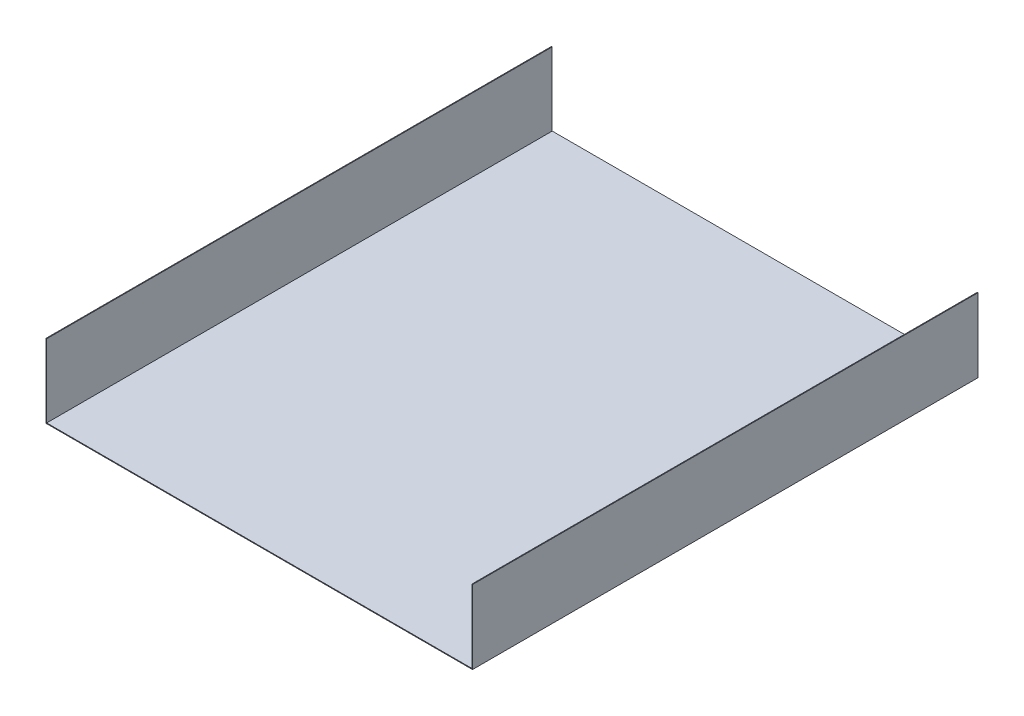
SolidWorks part; units mm, degrees
ref_plane "Front Plane" through (0, 0, 0) normal (0, 0, 1) x (1, 0, 0)
ref_plane "Top Plane" through (0, 0, 0) normal (0, 1, 0) x (1, 0, 0)
ref_plane "Right Plane" through (0, 0, 0) normal (1, 0, 0) x (0, 0, -1)
other "Configuration Table"
sketch "Sketch1" plane through (0, 0, 0) normal (0, 0, 1) x (1, 0, 0)
  line L0 (13.7, 106) -> (13.7, 4)
  line L1 (13.7, 4) -> (604.3, 4)
  line L2 (604.3, 4) -> (604.3, 106)
  line L3 (604.3, 106) -> (603.3, 106)
  line L4 (603.3, 106) -> (603.3, 5)
  line L5 (603.3, 5) -> (14.7, 5)
  line L6 (14.7, 5) -> (14.7, 106)
  line L7 (14.7, 106) -> (13.7, 106)
extrude "CEK_icecek_kutu_U_1.0_1" add sketch "Sketch1" against normal blind 700 separate body
